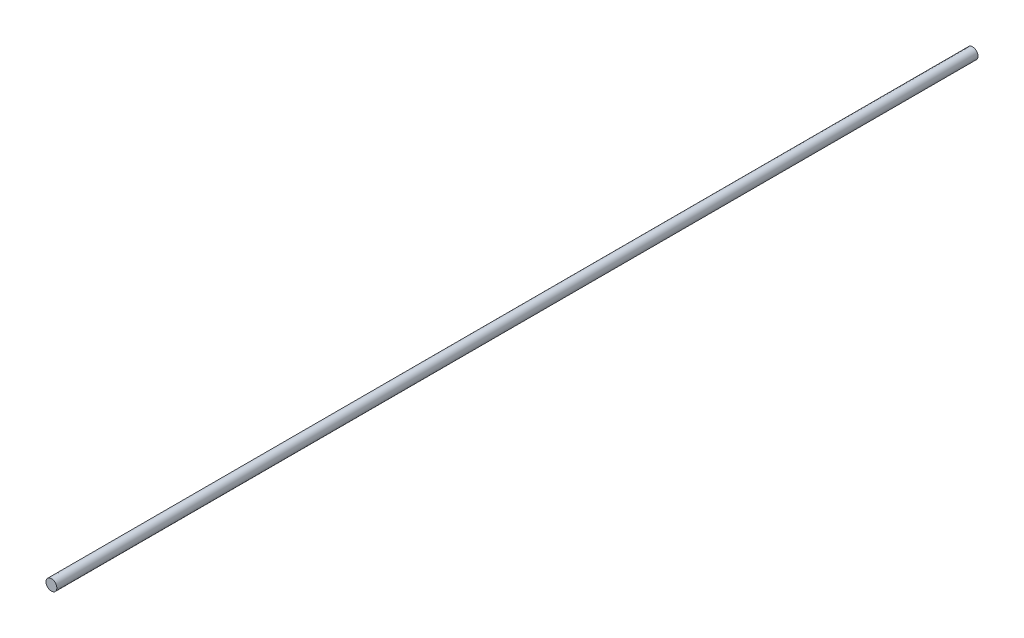
SolidWorks part; units mm, degrees
material "Manual Density from Real Component Perno alettone"
ref_plane "Piano frontale" through (0, 0, 0) normal (0, 0, 1) x (1, 0, 0)
ref_plane "Piano superiore" through (0, 0, 0) normal (0, 1, 0) x (1, 0, 0)
ref_plane "Piano destro" through (0, 0, 0) normal (1, 0, 0) x (0, 0, -1)
sketch "Schizzo1" plane through (0, 0, 0) normal (0, 0, 1) x (1, 0, 0)
  circle A0 centre (0, 0) radius 1.5
  dimension "D1" = 3
extrude "Estrusione-Estrusione1" add sketch "Schizzo1" along normal blind 255
